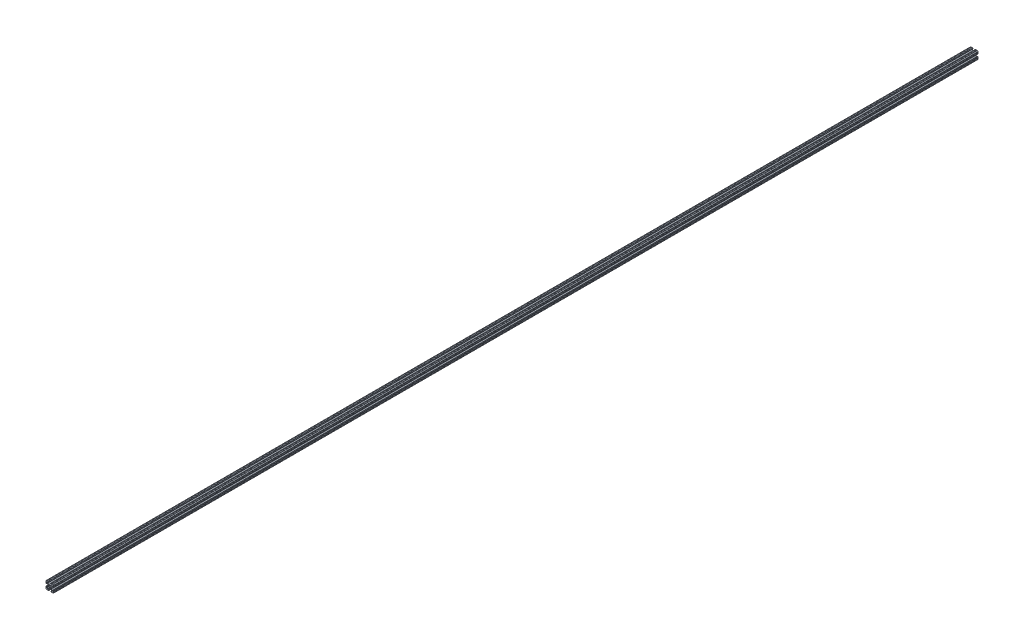
SolidWorks part; units mm, degrees
ref_plane "Front Plane" through (0, 0, 0) normal (0, 0, 1) x (1, 0, 0)
ref_plane "Top Plane" through (0, 0, 0) normal (0, 1, 0) x (1, 0, 0)
ref_plane "Right Plane" through (0, 0, 0) normal (1, 0, 0) x (0, 0, -1)
sketch "Sketch1" plane through (0, 0, 0) normal (0, 0, 1) x (1, 0, 0)
  line L88 (-7.1797, -8.6452) -> (-3.9523, -5.4237)
  line L89 (-1.7093, -4.4958) -> (1.7093, -4.4958)
  line L90 (3.9523, -5.4237) -> (7.1797, -8.6452)
  line L91 (6.4164, -10.4902) -> (4.2875, -10.4902)
  line L92 (3.2385, -11.5392) -> (3.2385, -11.651)
  line L93 (4.2875, -12.7) -> (5.3171, -12.7)
  line L94 (6.3331, -12.7) -> (9.5504, -12.7)
  line L95 (12.7, -9.5504) -> (12.7, -6.3331)
  line L96 (12.7, -5.3171) -> (12.7, -4.2875)
  line L97 (11.651, -3.2385) -> (11.5392, -3.2385)
  line L98 (10.4902, -4.2875) -> (10.4902, -6.4021)
  line L99 (8.7371, -7.1294) -> (5.441, -3.8408)
  line L100 (4.5085, -1.5932) -> (4.5085, 1.5932)
  line L101 (5.441, 3.8408) -> (8.7371, 7.1294)
  line L102 (10.4902, 6.4021) -> (10.4902, 4.2875)
  line L103 (11.5392, 3.2385) -> (11.651, 3.2385)
  line L104 (12.7, 4.2875) -> (12.7, 5.3171)
  line L105 (12.7, 6.3331) -> (12.7, 9.5504)
  line L106 (9.5504, 12.7) -> (6.3331, 12.7)
  line L107 (5.3171, 12.7) -> (4.2875, 12.7)
  line L108 (3.2385, 11.651) -> (3.2385, 11.5392)
  line L109 (4.2875, 10.4902) -> (6.4768, 10.4902)
  line L110 (7.207, 8.7244) -> (3.8983, 5.4232)
  line L111 (1.6558, 4.4958) -> (-1.6558, 4.4958)
  line L112 (-3.8983, 5.4232) -> (-7.207, 8.7244)
  line L113 (-6.4768, 10.4902) -> (-4.2875, 10.4902)
  line L114 (-3.2385, 11.5392) -> (-3.2385, 11.651)
  line L115 (-4.2875, 12.7) -> (-5.3171, 12.7)
  line L116 (-6.3331, 12.7) -> (-9.5504, 12.7)
  line L117 (-12.7, 9.5504) -> (-12.7, 6.3331)
  line L118 (-12.7, 5.3171) -> (-12.7, 4.2875)
  line L119 (-11.651, 3.2385) -> (-11.5392, 3.2385)
  line L120 (-10.4902, 4.2875) -> (-10.4902, 6.4021)
  line L121 (-8.7371, 7.1294) -> (-5.441, 3.8408)
  line L122 (-4.5085, 1.5932) -> (-4.5085, -1.5932)
  line L123 (-5.441, -3.8408) -> (-8.7371, -7.1294)
  line L124 (-10.4902, -6.4021) -> (-10.4902, -4.2875)
  line L125 (-11.5392, -3.2385) -> (-11.651, -3.2385)
  line L126 (-12.7, -4.2875) -> (-12.7, -5.3171)
  line L127 (-12.7, -6.3331) -> (-12.7, -9.5504)
  line L128 (-9.5504, -12.7) -> (-6.3331, -12.7)
  line L129 (-5.3171, -12.7) -> (-4.2875, -12.7)
  line L130 (-3.2385, -11.651) -> (-3.2385, -11.5392)
  line L131 (-4.2875, -10.4902) -> (-6.4164, -10.4902)
  circle A1 centre (0, 0) radius 2.6035
  arc A104 (-7.1797, -8.6452) -> (-6.4164, -10.4902) centre (-6.4164, -9.4098) ccw
  arc A105 (-1.7093, -4.4958) -> (-3.9523, -5.4237) centre (-1.7093, -7.6708) ccw
  arc A106 (3.9523, -5.4237) -> (1.7093, -4.4958) centre (1.7093, -7.6708) ccw
  arc A107 (6.4164, -10.4902) -> (7.1797, -8.6452) centre (6.4164, -9.4098) ccw
  arc A108 (4.2875, -10.4902) -> (3.2385, -11.5392) centre (4.2875, -11.5392) ccw
  arc A109 (3.2385, -11.651) -> (4.2875, -12.7) centre (4.2875, -11.651) ccw
  arc A110 (6.3331, -12.7) -> (5.3171, -12.7) centre (5.8251, -12.7) ccw
  arc A111 (10.5664, -12.6998) -> (9.5504, -12.7) centre (10.0584, -12.7) ccw
  arc A112 (10.5664, -12.6998) -> (12.6998, -10.5664) centre (10.5918, -10.5918) ccw
  arc A113 (12.7, -9.5504) -> (12.6998, -10.5664) centre (12.7, -10.0584) ccw
  arc A114 (12.7, -5.3171) -> (12.7, -6.3331) centre (12.7, -5.8251) ccw
  arc A115 (12.7, -4.2875) -> (11.651, -3.2385) centre (11.651, -4.2875) ccw
  arc A116 (11.5392, -3.2385) -> (10.4902, -4.2875) centre (11.5392, -4.2875) ccw
  arc A117 (8.7371, -7.1294) -> (10.4902, -6.4021) centre (9.4628, -6.4021) ccw
  arc A118 (4.5085, -1.5932) -> (5.441, -3.8408) centre (7.6835, -1.5932) ccw
  arc A119 (5.441, 3.8408) -> (4.5085, 1.5932) centre (7.6835, 1.5932) ccw
  arc A120 (10.4902, 6.4021) -> (8.7371, 7.1294) centre (9.4628, 6.4021) ccw
  arc A121 (10.4902, 4.2875) -> (11.5392, 3.2385) centre (11.5392, 4.2875) ccw
  arc A122 (11.651, 3.2385) -> (12.7, 4.2875) centre (11.651, 4.2875) ccw
  arc A123 (12.7, 6.3331) -> (12.7, 5.3171) centre (12.7, 5.8251) ccw
  arc A124 (12.6998, 10.5664) -> (12.7, 9.5504) centre (12.7, 10.0584) ccw
  arc A125 (12.6998, 10.5664) -> (10.5664, 12.6998) centre (10.5918, 10.5918) ccw
  arc A126 (9.5504, 12.7) -> (10.5664, 12.6998) centre (10.0584, 12.7) ccw
  arc A127 (5.3171, 12.7) -> (6.3331, 12.7) centre (5.8251, 12.7) ccw
  arc A128 (4.2875, 12.7) -> (3.2385, 11.651) centre (4.2875, 11.651) ccw
  arc A129 (3.2385, 11.5392) -> (4.2875, 10.4902) centre (4.2875, 11.5392) ccw
  arc A130 (7.207, 8.7244) -> (6.4768, 10.4902) centre (6.4768, 9.4563) ccw
  arc A131 (1.6558, 4.4958) -> (3.8983, 5.4232) centre (1.6558, 7.6708) ccw
  arc A132 (-3.8983, 5.4232) -> (-1.6558, 4.4958) centre (-1.6558, 7.6708) ccw
  arc A133 (-6.4768, 10.4902) -> (-7.207, 8.7244) centre (-6.4768, 9.4563) ccw
  arc A134 (-4.2875, 10.4902) -> (-3.2385, 11.5392) centre (-4.2875, 11.5392) ccw
  arc A135 (-3.2385, 11.651) -> (-4.2875, 12.7) centre (-4.2875, 11.651) ccw
  arc A136 (-6.3331, 12.7) -> (-5.3171, 12.7) centre (-5.8251, 12.7) ccw
  arc A137 (-10.5664, 12.6998) -> (-9.5504, 12.7) centre (-10.0584, 12.7) ccw
  arc A138 (-10.5664, 12.6998) -> (-12.6998, 10.5664) centre (-10.5918, 10.5918) ccw
  arc A139 (-12.7, 9.5504) -> (-12.6998, 10.5664) centre (-12.7, 10.0584) ccw
  arc A140 (-12.7, 5.3171) -> (-12.7, 6.3331) centre (-12.7, 5.8251) ccw
  arc A141 (-12.7, 4.2875) -> (-11.651, 3.2385) centre (-11.651, 4.2875) ccw
  arc A142 (-11.5392, 3.2385) -> (-10.4902, 4.2875) centre (-11.5392, 4.2875) ccw
  arc A143 (-8.7371, 7.1294) -> (-10.4902, 6.4021) centre (-9.4628, 6.4021) ccw
  arc A144 (-4.5085, 1.5932) -> (-5.441, 3.8408) centre (-7.6835, 1.5932) ccw
  arc A145 (-5.441, -3.8408) -> (-4.5085, -1.5932) centre (-7.6835, -1.5932) ccw
  arc A146 (-10.4902, -6.4021) -> (-8.7371, -7.1294) centre (-9.4628, -6.4021) ccw
  arc A147 (-10.4902, -4.2875) -> (-11.5392, -3.2385) centre (-11.5392, -4.2875) ccw
  arc A148 (-11.651, -3.2385) -> (-12.7, -4.2875) centre (-11.651, -4.2875) ccw
  arc A149 (-12.7, -6.3331) -> (-12.7, -5.3171) centre (-12.7, -5.8251) ccw
  arc A150 (-12.6998, -10.5664) -> (-12.7, -9.5504) centre (-12.7, -10.0584) ccw
  arc A151 (-12.6998, -10.5664) -> (-10.5664, -12.6998) centre (-10.5918, -10.5918) ccw
  arc A152 (-9.5504, -12.7) -> (-10.5664, -12.6998) centre (-10.0584, -12.7) ccw
  arc A153 (-5.3171, -12.7) -> (-6.3331, -12.7) centre (-5.8251, -12.7) ccw
  arc A154 (-4.2875, -12.7) -> (-3.2385, -11.651) centre (-4.2875, -11.651) ccw
  arc A155 (-3.2385, -11.5392) -> (-4.2875, -10.4902) centre (-4.2875, -11.5392) ccw
extrude "Boss-Extrude1" add sketch "Sketch1" along normal mid plane 3048
